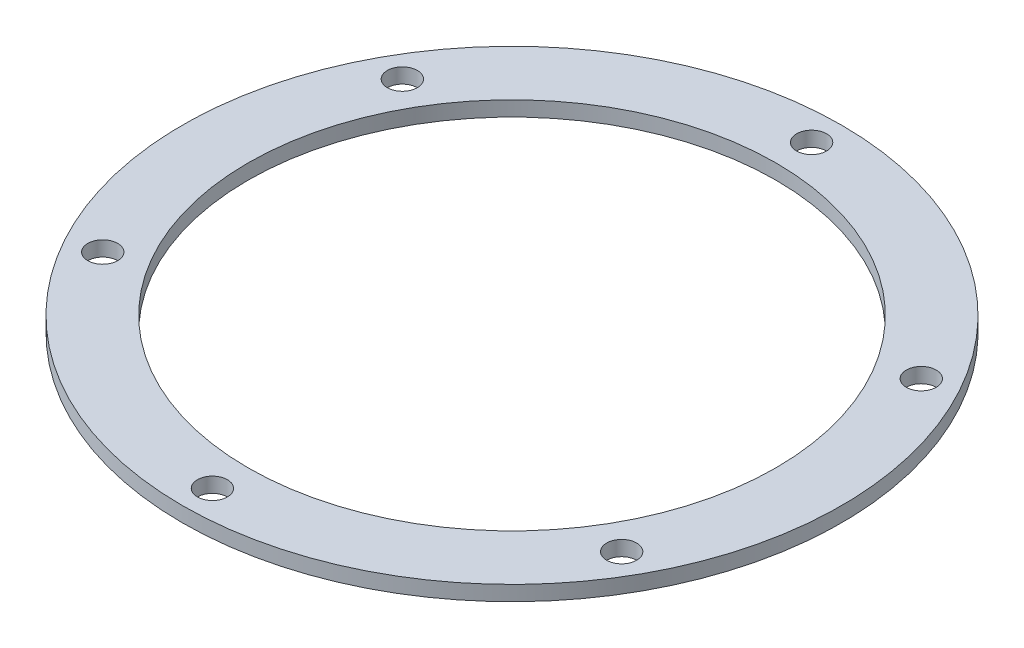
SolidWorks part; units mm, degrees
material "PLA"
ref_plane "Front Plane" through (0, 0, 0) normal (0, 0, 1) x (1, 0, 0)
ref_plane "Top Plane" through (0, 0, 0) normal (0, 1, 0) x (1, 0, 0)
ref_plane "Right Plane" through (0, 0, 0) normal (1, 0, 0) x (0, 0, -1)
sketch "Sketch1" plane through (0, 0, 0) normal (0, 1, 0) x (1, 0, 0)
  circle A0 centre (0, 0) radius 44
  circle A1 centre (0, 0) radius 35.25
  circle A2 centre (0, 0) radius 40 construction
  circle A3 centre (0, 40) radius 2
  circle A4 centre (34.641, 20) radius 2
  circle A5 centre (34.641, -20) radius 2
  circle A6 centre (0, -40) radius 2
  circle A7 centre (-34.641, -20) radius 2
  circle A8 centre (-34.641, 20) radius 2
  point P16 (0, 0)
  dimension "D1" = 70.5
  dimension "D3" = 80
  dimension "D4" = 4
  dimension "D2" = 8.75
  dimension "D5" = 6
extrude "Boss-Extrude1" add sketch "Sketch1" along normal blind 2
equation "\"Ns\"= 25"
equation "\"Np\"= 65"
equation "\"Nr\"= 155"
equation "\"num_planet\"= 3"
equation "\"module\"= 0.5"
equation "\"pressure angle\"= 20.0deg"
equation "\"h_a\"= 0.5"
equation "\"h_b\"= 0.625"
equation "\"clr_tip_root\"= 0.125"
equation "\"dp_s\"= 12.5"
equation "\"db_s\"= 11.746157759823856"
equation "\"fw_s_calc\"= 22.13479809822934"
equation "\"alpha_s\"= 0.8539582918412449"
equation "\"beta_s\"= 5.49208341631751"
equation "\"dp_p\"= 32.5"
equation "\"db_p\"= 30.540010175542022"
equation "\"fw_p\"= 22.13479809822934"
equation "\"alpha_p\"= 0.8539582918412485"
equation "\"beta_p\"= 1.0613141855482722"
equation "\"pressure_angle\"= 20.0deg"
equation "\"h_f\"= 0.625"
equation "\"dp_r\"= 77.5"
equation "\"db_r\"= 72.8261781109079"
equation "\"fw_r\"= 22.13479809822934"
equation "\"alpha_r\"= 0.8539582918412449"
equation "\"beta_r\"= 2.869206906263135"
equation "\"bearing_ID\"= 55"
equation "\"bearing_OD\"= 72"
equation "\"bearing_height\"= 9"
equation "\"clearance_planet\"= 1.5"
equation "\"case_dist\"= 6.5"
equation "\"Motor_case_OD_max\"= 112.3"
equation "\"case_mounting_PCD\"= 104.8"
equation "\"bearing mount thickness\"= 8"
equation "\"case_mounting_hole_dia\"= 3"
equation "\"output_mounting_PCD\"= 80"
equation "\"output_mounting_hole_dia\"= 4"
equation "\"clearance_case_mount_holes_shell_thickness\"= 1"
equation "\"motor_case_OD_base\"= 102.8"
equation "\"sec_carrier_thickness\"= 5"
equation "\"sun_coupler_hub_thickness\"= 4"
equation "\"clearance_sun_coupler_sec_carrier\"= 1.5"
equation "\"clearance_motor_and_case\"= 5"
equation "\"motor_OD\"= 87.8"
equation "\"Motor_case_thickness\"= 2.5"
equation "\"Motor_case_ID\"= 97.8"
equation "\"case_mounting_hole_shift\"= 1.0"
equation "\"output_mounting_nut_wrench_size\"= 7"
equation "\"output_mounting_nut_thickness\"= 3.2"
equation "\"case_mounting_hole_allen_socket_dia\"= 5.5"
equation "\"output_mounting_nut_depth\"= 3"
equation "\"case_mounting_bolt_depth\"= 4.5"
equation "\"ring_radial_thickness\"= 5.0"
equation "\"ring_OD\"= 87.5"
equation "\"ring_to_chamfer_clearance\"= 2"
equation "\"Motor_case_OD_base_to_chamfer\"= 5"
equation "\"pattern_offset_from_motor_case_OD_base\"= 3"
equation "\"pattern_bulge_dia\"= 3"
equation "\"pattern_num_bulge\"= 18"
equation "\"pattern_depth\"= 2"
equation "\"motor_height\"= 31.5"
equation "\"case_mounting_wrench_size\"= 5.5"
equation "\"case_mounting_nut_clearance\"= 2"
equation "\"base_plate_thickness\"= 4"
equation "\"case_mounting_nut_thickness\"= 2.4"
equation "\"case_mounting_surface_height\"= 4"
equation "\"motor_mount_hole_PCD\"= 36"
equation "\"motor_mount_hole_dia\"= 4"
equation "\"motor_mount_hole_num\"= 4"
equation "\"central_hole_offset_from_motor_mount_PCD\"= 5"
equation "\"wire_slot_dist_from_center\"= 40"
equation "\"wire_slot_length\"= 10"
equation "\"wire_slot_radius\"= 2.5"
equation "\"driver_upper_holes_dist_from_center\"= 29"
equation "\"driver_lower_holes_dist_from_center\"= 13"
equation "\"driver_side_holes_dist_from_center\"= 22.5"
equation "\"driver_mount_holes_dia\"= 3"
equation "\"driver_mount_inserts_OD\"= 4.8"
equation "\"driver_mount_thickness\"= 1.5"
equation "\"driver_mount_height\"= 6"
equation "\"air_flow_hole_offset\"= 3"
equation "\"planet_pin_bolt_dia\"= 5"
equation "\"planet_pin_socket_head_dia\"= 8.5"
equation "\"carrier_PCD\"= 45.0"
equation "\"planet_shaft_dia\"= 8"
equation "\"planet_shaft_step_offset\"= 1"
equation "\"carrier_trapezoidal_support_sun_offset\"= 5"
equation "\"carrier_trapezoidal_support_hole_PCD_offset_bearing_ID\"= 4"
equation "\"carrier_trapezoidal_support_hole_dia\"= 3"
equation "\"carrier_trapezoidal_support_hole_socket_head_dia\"= 5.5"
equation "\"carrier_bearing_step_width\"= 1.5"
equation "\"standard_clearance_1_5mm\"= 1.5"
equation "\"standard_fillet_1_5mm\"= 1.5"
equation "\"sun_shaft_bearing_OD\"= 16"
equation "\"sun_shaft_bearing_width\"= 5"
equation "\"standard_bearing_insertion_chamfer\"= 0.5"
equation "\"carrier_trapezoidal_support_hole_wrench_size\"= 5.5"
equation "\"planet_pin_bolt_wrench_size\"= 8"
equation "\"planet_bearing_OD\"= 12"
equation "\"planet_bearing_width\"= 3.5"
equation "\"planet_bore\"= 10"
equation "\"motor_output_hole_PCD\"= 23"
equation "\"motor_output_hole_dia\"= 4"
equation "\"motor_output_hole_num\"= 4"
equation "\"sun_shaft_bearing_ID\"= 8"
equation "\"sun_hub_dia\"= 33.0"
equation "\"sun_central_bolt_dia\"= 5"
equation "\"sun_central_bolt_socket_head_dia\"= 8.5"
equation "\"fw_s_used\"= 30.13479809822934"
equation "\"motor_output_hole_CSK_OD\"= 8"
equation "\"motor_output_hole_CSK_head_height\"= 2.0"
equation "\"D1@Sketch1\"=\"bearing_OD\"-\"standard_clearance_1_5mm\""
equation "\"D2@Sketch1\"=\"bearing mount thickness\"+\"standard_clearance_1_5mm\"/2"
equation "\"D3@Sketch1\"=\"output_mounting_PCD\""
equation "\"D4@Sketch1\"=\"output_mounting_hole_dia\""
equation "\"bearing_retainer_thickness\"= 2"
equation "\"D1@Boss-Extrude1\"=\"bearing_retainer_thickness\""
